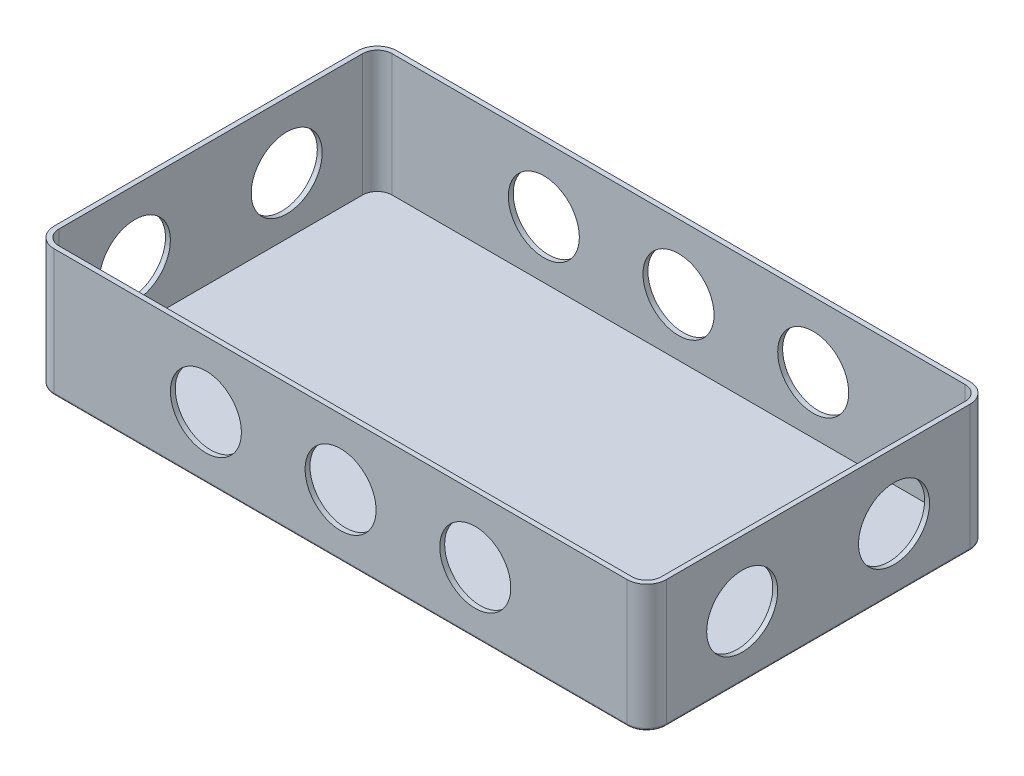
SolidWorks part; units mm, degrees
material "PBT General Purpose"
ref_plane "Front Plane" through (0, 0, 0) normal (0, 0, 1) x (1, 0, 0)
ref_plane "Top Plane" through (0, 0, 0) normal (0, 1, 0) x (1, 0, 0)
ref_plane "Right Plane" through (0, 0, 0) normal (1, 0, 0) x (0, 0, -1)
sketch "Sketch1" plane through (0, 0, 0) normal (0, 1, 0) x (1, 0, 0)
  line L0 (0, 70) -> (0, 0) construction
  line L1 (0, 0) -> (125, 0) construction
  line L2 (125, -62) -> (125, 62)
  line L3 (117, 70) -> (-117, 70)
  line L4 (-125, -62) -> (-125, 62)
  line L5 (117, -70) -> (-117, -70)
  arc A0 (125, 62) -> (117, 70) centre (117, 62) ccw
  arc A1 (-125, 62) -> (-117, 70) centre (-117, 62) cw
  arc A2 (-125, -62) -> (-117, -70) centre (-117, -62) ccw
  arc A3 (125, -62) -> (117, -70) centre (117, -62) cw
  point P17 (-125, 0)
  dimension "D1" = 8
  dimension "D2" = 140
  dimension "D3" = 250
extrude "Boss-Extrude1" add sketch "Sketch1" along normal blind 52
fillet "Fillet1" radius 1 8 edges at (-122.6569, 0, 67.6569) (-125, 0, 0) (-122.6569, 0, -67.6569) (0, 0, -70) (122.6569, 0, -67.6569) (125, 0, 0) (122.6569, 0, 67.6569) (0, 0, 70)
shell "Shell1" thickness 2
sketch "Sketch2" plane through (0, 0, 0) normal (0, -1, 0) x (1, 0, 0)
  line L0 (0, 64.6316) -> (0, 0) construction
  line L1 (0, 0) -> (65.5067, 0) construction
  circle A0 centre (76, 51) radius 4
  circle A1 centre (76, 51) radius 9
  circle A2 centre (76, -51) radius 9
  circle A3 centre (76, -51) radius 4
  circle A4 centre (-76, -51) radius 4
  circle A5 centre (-76, -51) radius 9
  circle A6 centre (-76, 51) radius 9
  circle A7 centre (-76, 51) radius 4
  dimension "D1" = 8
  dimension "D2" = 18
  dimension "D3" = 152
  dimension "D4" = 102
extrude "Boss-Extrude2" add sketch "Sketch2" along normal blind 2.5
sketch "Sketch3" plane through (0, 0, -70) normal (0, 0, -1) x (-1, 0, 0)
  line L0 (0, 0) -> (0, 69.3908) construction
  line L1 (-117, 52) -> (117, 52) construction
  circle A0 centre (-55, 25.3) radius 14.5
  circle A1 centre (0, 25.3) radius 14.5
  circle A2 centre (55, 25.3) radius 14.5
  dimension "D1" = 29
  dimension "D3" = 81
  dimension "D2" = 12.2
extrude "Cut-Extrude1" cut sketch "Sketch3" against normal through all
sketch "Sketch4" plane through (0, 0, 0) normal (1, 0, 0) x (0, 0, -1)
  line L0 (0, 0) -> (0, 62.8314) construction
  line L1 (-62, 52) -> (62, 52) construction
  circle A0 centre (31, 25.3) radius 14.5
  circle A1 centre (-31, 25.3) radius 14.5
  dimension "D1" = 29
  dimension "D2" = 33
  dimension "D3" = 12.2
extrude "Cut-Extrude2" cut sketch "Sketch4" against normal through all and the other way through all
